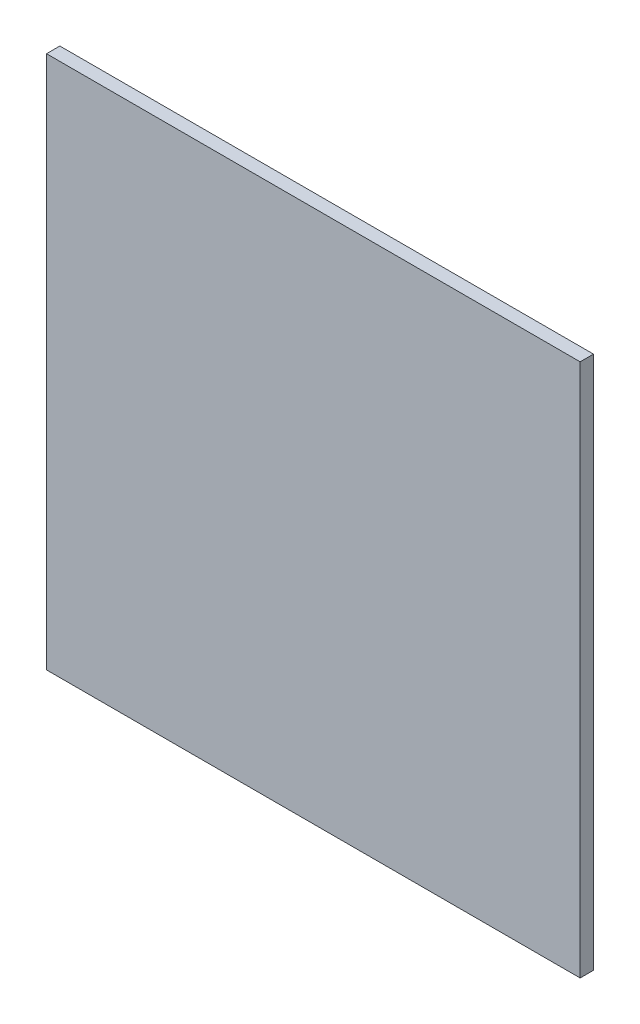
SolidWorks part; units mm, degrees
ref_plane "Спереди" through (0, 0, 0) normal (0, 0, 1) x (1, 0, 0)
ref_plane "Сверху" through (0, 0, 0) normal (0, 1, 0) x (1, 0, 0)
ref_plane "Справа" through (0, 0, 0) normal (1, 0, 0) x (0, 0, -1)
other "Configuration Table"
sketch "Эскиз1" plane through (0, 0, 0) normal (0, 0, 1) x (1, 0, 0)
  line L0 (-60, 60) -> (60, -60) construction
  line L1 (-60, 60) -> (60, 60)
  line L2 (-60, 60) -> (-60, -60)
  line L3 (-60, -60) -> (60, -60)
  line L4 (60, 60) -> (60, -60)
  line L5 (60, 60) -> (-60, -60) construction
  point P4 (0, 0)
  dimension "D1" = 120
  dimension "D2" = 120
extrude "Бобышка-Вытянуть1" add sketch "Эскиз1" along normal blind 3
